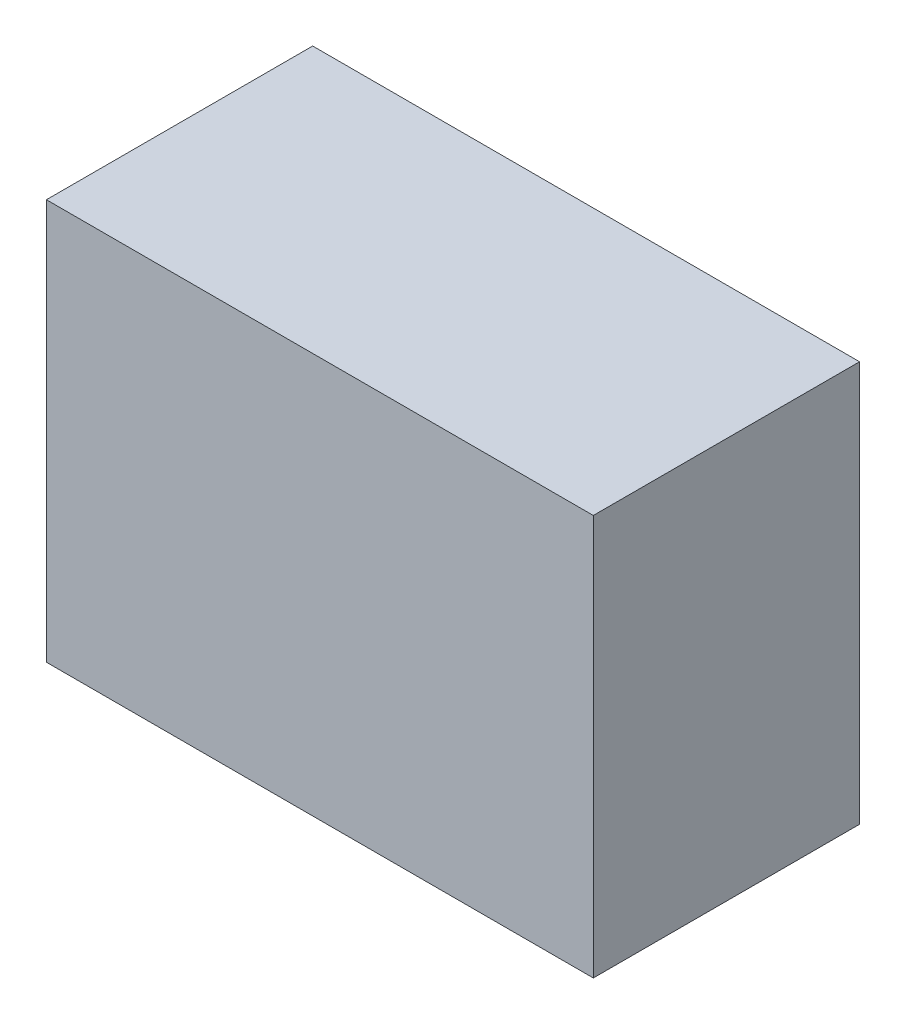
SolidWorks part; units mm, degrees
ref_plane "Front Plane" through (0, 0, 0) normal (0, 0, 1) x (1, 0, 0)
ref_plane "Top Plane" through (0, 0, 0) normal (0, 1, 0) x (1, 0, 0)
ref_plane "Right Plane" through (0, 0, 0) normal (1, 0, 0) x (0, 0, -1)
sketch "Sketch3" plane through (0, 0, 0) normal (0, 0, 1) x (1, 0, 0)
  line L1 (0, 0) -> (45.6, 0)
  line L2 (0, 0) -> (0, 33.4)
  line L3 (0, 33.4) -> (45.6, 33.4)
  line L4 (45.6, 0) -> (45.6, 33.4)
  dimension "D1" = 33.4
  dimension "D2" = 45.6
extrude "Boss-Extrude1" add sketch "Sketch3" along normal blind 22.2
